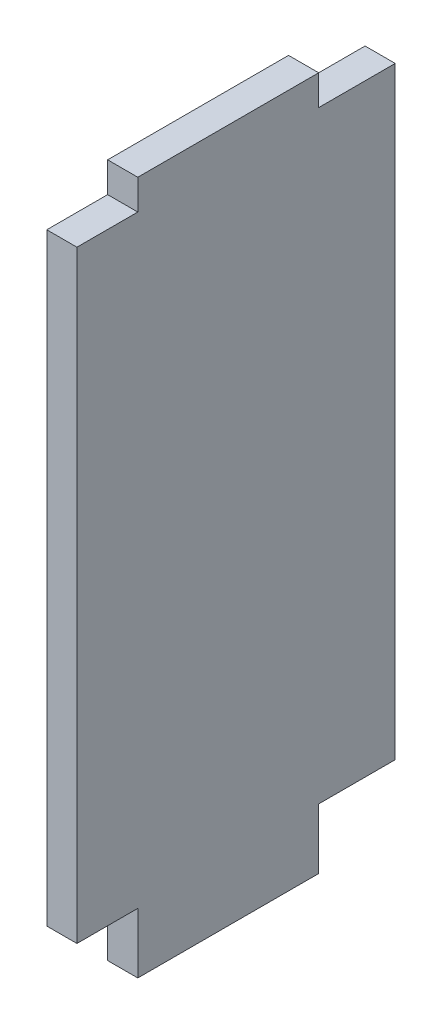
SolidWorks part; units mm, degrees
material "Maple"
ref_plane "Front Plane" through (0, 0, 0) normal (0, 0, 1) x (1, 0, 0)
ref_plane "Top Plane" through (0, 0, 0) normal (0, 1, 0) x (1, 0, 0)
ref_plane "Right Plane" through (0, 0, 0) normal (1, 0, 0) x (0, 0, -1)
sketch "Sketch1" plane through (0, 0, 0) normal (1, 0, 0) x (0, 0, -1)
  line L0 (-7.6594, 0) -> (6.6904, 0) construction
  line L1 (-13.195, -25) -> (13.195, -25) construction
  line L2 (-13.195, -25) -> (-13.195, 25)
  line L3 (-13.195, 25) -> (13.195, 25) construction
  line L4 (13.195, -25) -> (13.195, 25)
  line L5 (-13.195, -25) -> (13.195, 25) construction
  line L6 (-13.195, 25) -> (13.195, -25) construction
  line L7 (-13.195, 27.5) -> (13.195, 27.5) construction
  line L8 (-13.195, -30) -> (13.195, -30) construction
  line L9 (-13.195, 25) -> (-8.1495, 25)
  line L10 (-8.1495, 25) -> (-8.1495, 27.5)
  line L11 (-8.1495, 27.5) -> (6.8505, 27.5)
  line L12 (6.8505, 27.5) -> (6.8505, 25)
  line L13 (6.8505, 25) -> (13.195, 25)
  line L14 (6.8505, -25) -> (13.195, -25)
  line L15 (6.8505, -30) -> (6.8505, -25)
  line L16 (-8.1495, -30) -> (6.8505, -30)
  line L17 (-13.195, -25) -> (-8.1495, -25)
  line L18 (-8.1495, -25) -> (-8.1495, -30)
  point P0 (0, 0)
  dimension "D1" = 26.39
  dimension "D2" = 50
  dimension "D5" = 15
  dimension "D6" = 6.3445
  dimension "D3" = 2.5
  dimension "D4" = 5
extrude "Boss-Extrude1" add sketch "Sketch1" along normal mid plane 2.5
